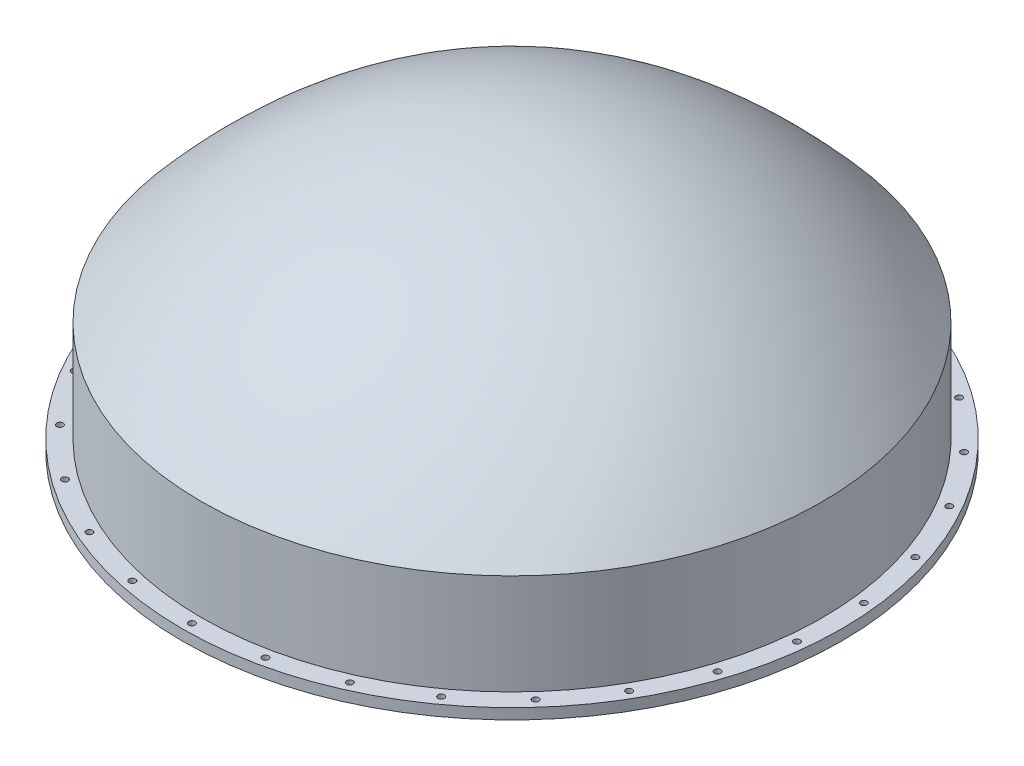
SolidWorks part; units mm, degrees
ref_plane "Front Plane" through (0, 0, 0) normal (0, 0, 1) x (1, 0, 0)
ref_plane "Top Plane" through (0, 0, 0) normal (0, 1, 0) x (1, 0, 0)
ref_plane "Right Plane" through (0, 0, 0) normal (1, 0, 0) x (0, 0, -1)
sketch "Sketch1" plane through (0, 0, 0) normal (1, 0, 0) x (0, 0, -1)
  line L0 (1887.5407, 0) -> (0, 0) construction
  line L1 (0, 0) -> (0, 2161.6793) construction
  line L2 (-2081.13, 0) -> (-2081.13, -744.115)
  line L3 (-931.3985, 1044.41) -> (931.3985, 1044.41) construction
  line L4 (-2130.02, 18.4154) -> (-2130.02, -671.115)
  line L5 (-2081.13, -744.115) -> (-2262.02, -744.115)
  line L6 (-2262.02, -744.115) -> (-2262.02, -671.115)
  line L7 (-2262.02, -671.115) -> (-2130.02, -671.115)
  line L8 (0, 1093.3) -> (0, 1044.41)
  line L9 (-2130.02, 18.4154) -> (-2130.02, -744.115) construction
  spline S0 degree 2 poles (0, 1044.41) (-1164.2481, 1044.41) (-2081.13, 0) knots 0 0 0 1 1 1
  spline S1 degree 1 poles (0, 1093.3) (-2130.02, 18.4154) knots 0 0 1 1 construction
  spline S2 degree 3 poles (0, 1093.3) (-12.4185, 1093.3) (-37.2831, 1093.1245) (-86.7847, 1092.0713) (-148.3895, 1089.4377) (-221.8274, 1084.1687) (-294.7872, 1076.7903) (-367.2617, 1067.3017) (-463.2435, 1051.8365) (-581.9905, 1027.2289) (-722.4876, 989.2625) (-860.9563, 942.8689) (-997.3697, 888.0628) (-1131.7056, 824.8627) (-1263.9462, 753.2896) (-1394.0791, 673.3657) (-1522.097, 585.1132) (-1647.9972, 488.5533) (-1751.1504, 401.18) (-1832.6171, 327.1456) (-1893.1899, 269.5539) (-1953.2365, 209.898) (-2002.8378, 158.4658) (-2042.2567, 116.2895) (-2066.7847, 89.4997) (-2086.341, 67.8111) (-2098.5381, 54.1468) (-2108.2758, 43.1548) (-2114.3635, 36.2493) (-2119.2103, 30.7286) (-2124.0074, 25.2642) (-2127.6165, 21.1532) (-2130.02, 18.4154) knots 0 0 0 0 0.015729 0.031457 0.062914 0.094371 0.125828 0.157285 0.188742 0.251656 0.31457 0.377484 0.440399 0.503313 0.566227 0.629141 0.692055 0.754969 0.817883 0.84934 0.880797 0.912254 0.943711 0.95944 0.975168 0.983033 0.990897 0.994829 0.998761 1.000727 1.002693 1.006625 1.006625 1.006625 1.006625
  dimension "D1" = 2081.13
  dimension "D2" = 1044.41
  dimension "D3" = 744.115
  dimension "D5" = 132
  dimension "D6" = 73
  dimension "D4" = 48.89
revolve "Revolve1" add sketch "Sketch1" angle 360 about L8
sketch "Sketch2" plane through (0, -744.115, 0) normal (0, -1, 0) x (1, 0, 0)
  circle A0 centre (0, 0) radius 2196.0235 construction
  circle A1 centre (0, 2196.0235) radius 22
  circle A2 centre (456.579, 2148.0351) radius 22
  circle A3 centre (893.2032, 2006.1673) radius 22
  circle A4 centre (1290.7902, 1776.6203) radius 22
  circle A5 centre (1631.9635, 1469.4265) radius 22
  circle A6 centre (1901.8121, 1098.0118) radius 22
  circle A7 centre (2088.5425, 678.6086) radius 22
  circle A8 centre (2183.9935, 229.547) radius 22
  circle A9 centre (2183.9935, -229.547) radius 22
  circle A10 centre (2088.5425, -678.6086) radius 22
  circle A11 centre (1901.8121, -1098.0117) radius 22
  circle A12 centre (1631.9635, -1469.4265) radius 22
  circle A13 centre (1290.7902, -1776.6203) radius 22
  circle A14 centre (893.2032, -2006.1673) radius 22
  circle A15 centre (456.579, -2148.0351) radius 22
  circle A16 centre (0, -2196.0235) radius 22
  circle A17 centre (-456.579, -2148.0351) radius 22
  circle A18 centre (-893.2032, -2006.1673) radius 22
  circle A19 centre (-1290.7902, -1776.6203) radius 22
  circle A20 centre (-1631.9635, -1469.4265) radius 22
  circle A21 centre (-1901.8121, -1098.0118) radius 22
  circle A22 centre (-2088.5425, -678.6086) radius 22
  circle A23 centre (-2183.9935, -229.547) radius 22
  circle A24 centre (-2183.9935, 229.547) radius 22
  circle A25 centre (-2088.5425, 678.6086) radius 22
  circle A26 centre (-1901.8121, 1098.0117) radius 22
  circle A27 centre (-1631.9635, 1469.4265) radius 22
  circle A28 centre (-1290.7902, 1776.6203) radius 22
  circle A29 centre (-893.2032, 2006.1673) radius 22
  circle A30 centre (-456.579, 2148.0351) radius 22
  point P66 (0, 0)
  dimension "D1" = 44
  dimension "D2" = 30
extrude "Cut-Extrude1" cut sketch "Sketch2" against normal up to next (73 mm away)
